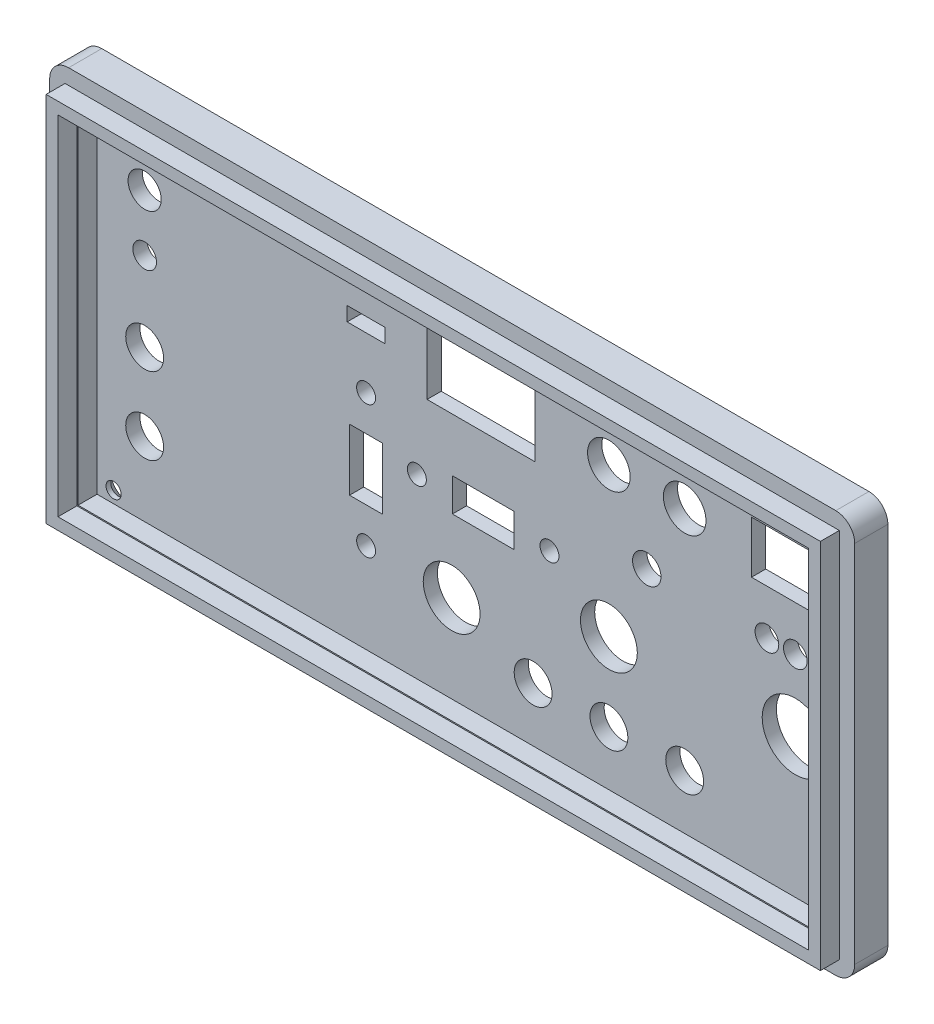
SolidWorks part; units mm, degrees
ref_plane "Спереди" through (0, 0, 0) normal (0, 0, 1) x (1, 0, 0)
ref_plane "Сверху" through (0, 0, 0) normal (0, 1, 0) x (1, 0, 0)
ref_plane "Справа" through (0, 0, 0) normal (1, 0, 0) x (0, 0, -1)
other "Configuration Table"
sketch "Эскиз1" plane through (0, 0, 0) normal (0, 0, 1) x (1, 0, 0)
  line L1 (-85, 42.5) -> (85, 42.5)
  line L2 (-85, 42.5) -> (-85, -42.5)
  line L3 (-85, -42.5) -> (85, -42.5)
  line L4 (85, 42.5) -> (85, -42.5)
  line L5 (-85, 42.5) -> (85, -42.5) construction
  line L6 (-85, -42.5) -> (85, 42.5) construction
  point P0 (0, 0)
  dimension "D1" = 170
  dimension "D2" = 85
extrude "Бобышка-Вытянуть1" add sketch "Эскиз1" along normal blind 3
sketch "Эскиз2" plane through (0, 0, 3) normal (0, 0, 1) x (1, 0, 0)
  line L1 (-85, 42.5) -> (85, 42.5)
  line L2 (-85, 42.5) -> (-85, -42.5)
  line L3 (-85, -42.5) -> (85, -42.5)
  line L4 (85, 42.5) -> (85, -42.5)
  line L5 (-85, 42.5) -> (85, -42.5) construction
  line L6 (-85, -42.5) -> (85, 42.5) construction
  point P0 (0, 0)
extrude "Вытянуть-Тонкостенный1" add sketch "Эскиз2" along normal blind 4 thin
sketch "Эскиз4" plane through (0, 0, 7) normal (0, 0, 1) x (1, 0, 0)
  line L1 (-81.75, 39.25) -> (81.75, 39.25)
  line L2 (-81.75, 39.25) -> (-81.75, -39.25)
  line L3 (-81.75, -39.25) -> (81.75, -39.25)
  line L4 (81.75, 39.25) -> (81.75, -39.25)
  line L5 (-81.75, 39.25) -> (81.75, -39.25) construction
  line L6 (-81.75, -39.25) -> (81.75, 39.25) construction
  point P0 (0, 0)
  dimension "D1" = 78.5
  dimension "D2" = 163.5
extrude "Вытянуть-Тонкостенный2" add sketch "Эскиз4" along normal blind 4 thin
fillet "Скругление1" radius 4 4 edges at (-85, -42.5, 3.5) (-85, 42.5, 3.5) (85, 42.5, 3.5) (85, -42.5, 3.5)
ref_plane "Плоскость1" through (82.5, -40, 37) normal (-1, 0, 0) x (0, 0, 1)
sketch "Эскиз7" plane through (0, 0, 38.5) normal (0, 0, 1) x (1, 0, 0)
  circle A0 centre (-75.5, 34) radius 1.6
sketch "Эскиз8" plane through (0, 0, 3) normal (0, 0, 1) x (1, 0, 0)
  circle A0 centre (-75.5, 34) radius 1.6
  circle A1 centre (75.5717, 35.0096) radius 1.6
  circle A2 centre (75.5717, -32.9904) radius 1.6
  circle A3 centre (-75.5, -34) radius 1.6
  dimension "D1" = 3.2
  dimension "D2" = 3.2
  dimension "D3" = 3.2
  dimension "D4" = 3.2
extrude "Вырез-Вытянуть1" cut sketch "Эскиз8" against normal blind 10
chamfer "Фаска1" distance 2 angle 45 4 edges at (77.1717, -32.9904, 0) (77.1717, 35.0096, 0) (-73.9, 34, 0) (-73.9, -34, 0)
sketch "Эскиз9" plane through (0, 0, 0) normal (0, 0, -1) x (-1, 0, 0)
  line L0 (-97.6837, 22.9271) -> (103.9627, 22.9271) construction
  line L1 (-68.4596, 22.9271) -> (-68.4596, -4.7615) construction
  line L2 (-97.6837, 7.9271) -> (103.9627, 7.9271) construction
  line L3 (-77.7096, 28.4271) -> (-59.2096, 28.4271)
  line L4 (-77.7096, 28.4271) -> (-77.7096, 17.4271)
  line L5 (-77.7096, 17.4271) -> (-59.2096, 17.4271)
  line L6 (-59.2096, 28.4271) -> (-59.2096, 17.4271)
  line L7 (-77.7096, 28.4271) -> (-59.2096, 17.4271) construction
  line L8 (-77.7096, 17.4271) -> (-59.2096, 28.4271) construction
  line L9 (-97.6837, -7.0729) -> (103.9627, -7.0729) construction
  circle A0 centre (-74.4596, 7.9271) radius 2.5
  circle A1 centre (-68.4596, 7.9271) radius 2.5
  circle A2 centre (-62.4596, 7.9271) radius 2.5
  circle A3 centre (-68.4596, -7.0729) radius 7
  point P7 (-68.4596, 22.9271)
  dimension "D1" = 30
  dimension "D2" = 11
  dimension "D3" = 15
extrude "Вырез-Оптопари" cut sketch "Эскиз9" against normal blind 10
sketch "Эскиз10" plane through (0, 0, 0) normal (0, 0, -1) x (-1, 0, 0)
  line L0 (-77.7096, 22.9271) -> (99.4949, 22.9271) construction
  line L1 (-77.7096, 28.4271) -> (-77.7096, 17.4271) construction
  line L2 (-74.4596, 7.9271) -> (86.7696, 7.9271) construction
  circle A0 centre (-45.0907, 22.9271) radius 4.5
  circle A1 centre (-29.0907, 22.9271) radius 4.5
  circle A2 centre (-37.0907, 7.9271) radius 3
  dimension "D1" = 16
  dimension "D2" = 8
extrude "Вырез-Стабілітрон" cut sketch "Эскиз10" against normal blind 10
sketch "Эскиз12" plane through (0, 0, 0) normal (0, 0, -1) x (-1, 0, 0)
  line L0 (-45.0907, 22.9271) -> (90.0896, 22.9271) construction
  line L1 (-45.5401, 0.9041) -> (54.3587, 0.9041) construction
  line L2 (-13.4907, 30.1771) -> (9.3093, 30.1771)
  line L3 (-13.4907, 30.1771) -> (-13.4907, 15.6771)
  line L4 (-13.4907, 15.6771) -> (9.3093, 15.6771)
  line L5 (9.3093, 30.1771) -> (9.3093, 15.6771)
  line L6 (-13.4907, 30.1771) -> (9.3093, 15.6771) construction
  line L7 (-13.4907, 15.6771) -> (9.3093, 30.1771) construction
  line L9 (-9.0401, 4.4041) -> (3.9599, 4.4041)
  line L10 (-9.0401, 4.4041) -> (-9.0401, -2.5959)
  line L11 (-9.0401, -2.5959) -> (3.9599, -2.5959)
  line L12 (3.9599, 4.4041) -> (3.9599, -2.5959)
  line L13 (-9.0401, 4.4041) -> (3.9599, -2.5959) construction
  line L14 (-9.0401, -2.5959) -> (3.9599, 4.4041) construction
  circle A0 centre (-16.5401, 0.9041) radius 2
  circle A1 centre (11.4599, 0.9041) radius 2
  point P3 (-2.0907, 22.9271)
  point P10 (-2.5401, 0.9041)
  dimension "D6" = 14
  dimension "D1" = 22.8
  dimension "D2" = 14.5
  dimension "D3" = 43
  dimension "D4" = 7
  dimension "D5" = 13
  dimension "D7" = 14
extrude "Вырез-Вольтметр" cut sketch "Эскиз12" against normal blind 10
sketch "Эскиз14" plane through (0, 0, 0) normal (0, 0, -1) x (-1, 0, 0)
  line L0 (-45.6627, 34.8723) -> (-45.6627, 33.8723)
  line L1 (-45.6627, 34.8723) -> (-39.6627, 34.8723)
  line L2 (-45.6627, 33.8723) -> (-39.6627, 33.8723)
  line L3 (-39.6627, 34.8723) -> (-39.6627, 37.8723)
  line L4 (-39.6627, 33.8723) -> (-39.6627, 30.8723)
  line L5 (-45.6627, 34.3723) -> (-30.2998, 34.3723) construction
  line L6 (-39.6627, 30.8723) -> (-34.9468, 33.8723)
  line L7 (-39.6627, 37.8723) -> (-34.9468, 34.8723)
  line L14 (-34.9468, 30.8723) -> (-34.9468, 33.8723)
  line L20 (-34.9468, 34.8723) -> (-34.9468, 37.6358)
  line L21 (-34.9468, 37.6358) -> (-36.1646, 37.6358)
  line L22 (-36.1646, 37.6358) -> (-36.1646, 38.3762)
  line L23 (-36.1646, 38.3762) -> (-34.0443, 38.3762)
  line L24 (-34.0443, 38.3762) -> (-34.0443, 34.8723)
  line L25 (-34.0443, 34.8723) -> (-30.2998, 34.8723)
  line L26 (-30.2998, 34.8723) -> (-30.2998, 33.8723)
  line L27 (-30.2998, 33.8723) -> (-34.0443, 33.8723)
  line L28 (-34.0443, 33.8723) -> (-34.0443, 30.8723)
  line L29 (-34.9468, 30.8723) -> (-34.0443, 30.8723)
extrude "Вырез-Символ стабілітрон" cut sketch "Эскиз14" against normal blind 1
sketch "Эскиз15" plane through (0, 0, 0) normal (0, 0, -1) x (-1, 0, 0)
  line L0 (-85, -25) -> (92.6455, -25) construction
  line L1 (-85, -38.5) -> (-85, 38.5) construction
  line L2 (-45.0907, 22.9271) -> (-45.0907, -33.3708) construction
  line L3 (-29.0907, 22.9271) -> (-29.0907, -33.3708) construction
  line L4 (-13.0907, 22.9271) -> (-13.0907, -33.3708) construction
  circle A0 centre (-45.0907, -25) radius 4
  circle A1 centre (-29.0907, -25) radius 4
  circle A2 centre (-13.0907, -25) radius 4
  circle A3 centre (-29.0907, -8.4792) radius 6
  dimension "D2" = 25
  dimension "D1" = 16
extrude "Вырез-MOSFET_TRIAC" cut sketch "Эскиз15" against normal blind 4
sketch "Эскиз16" plane through (0, 0, 0) normal (0, 0, -1) x (-1, 0, 0)
  text T0 "<b>G</b>"
  text T1 "<b>D</b>"
  text T2 "<b>S</b>"
  point P2 (0, 0)
  point P3 (0, 0)
  point P5 (-16.1508, -35.7077)
  point P6 (-14.9612, -33.6029)
  point P7 (0, 0)
  point P8 (-15.6018, -34.7011)
  point P9 (-47.7222, -34.7011)
extrude "Вырез-GDS" cut sketch "Эскиз16" against normal blind 1
sketch "Эскиз17" plane through (0, 0, 0) normal (0, 0, -1) x (-1, 0, 0)
  line L0 (-91.259, -18) -> (28.0286, -18) construction
  circle A0 centre (4.1179, -18) radius 6
  dimension "D1" = 18
extrude "Вырез-Нагрузочна лампа" cut sketch "Эскиз17" against normal blind 5
sketch "Эскиз18" plane through (0, 0, 0) normal (0, 0, -1) x (-1, 0, 0)
  line L0 (-77.7096, 22.9271) -> (77.7492, 22.9271) construction
  line L1 (-77.7096, 28.4271) -> (-77.7096, 17.4271) construction
  line L2 (22.1808, 22.9271) -> (22.1808, -29.9699) construction
  line L3 (18.1808, 24.4271) -> (26.1808, 24.4271)
  line L4 (18.1808, 24.4271) -> (18.1808, 21.4271)
  line L5 (18.1808, 21.4271) -> (26.1808, 21.4271)
  line L6 (26.1808, 24.4271) -> (26.1808, 21.4271)
  line L7 (18.1808, 24.4271) -> (26.1808, 21.4271) construction
  line L8 (18.1808, 21.4271) -> (26.1808, 24.4271) construction
  line L9 (11.4599, 0.9041) -> (11.4599, -7.0412) construction
  line L11 (18.6808, 2.9786) -> (25.6808, 2.9786)
  line L12 (18.6808, 2.9786) -> (18.6808, -10.0214)
  line L13 (18.6808, -10.0214) -> (25.6808, -10.0214)
  line L14 (25.6808, 2.9786) -> (25.6808, -10.0214)
  line L15 (18.6808, 2.9786) -> (25.6808, -10.0214) construction
  line L16 (18.6808, -10.0214) -> (25.6808, 2.9786) construction
  circle A0 centre (22.1808, 10.4786) radius 2
  circle A1 centre (22.1808, -17.5214) radius 2
  point P4 (22.1808, 22.9271)
  point P14 (22.1808, -3.5214)
  point P23 (0, 0)
  point P24 (0, 0)
  point P25 (22.1808, -3.5214)
  dimension "D6" = 14
  dimension "D1" = 8
  dimension "D2" = 3
  dimension "D3" = 10.721
  dimension "D4" = 7
  dimension "D5" = 13
  dimension "D7" = 14
extrude "Вырез-Вытянуть9" cut sketch "Эскиз18" against normal blind 5
sketch "Эскиз19" plane through (0, 0, 0) normal (0, 0, -1) x (-1, 0, 0)
  text T0 "<b>TL431</b>" font "Arial" height 3
  text T1 "<b>R A C</b>" font "Arial" height 3
  text T2 "<b>2.5V</b>"
  text T3 "<b>5V</b>"
  point P4 (27.1543, -8.3295)
extrude "Вырез-Вытянуть10" cut sketch "Эскиз19" against normal blind 1
sketch "Эскиз20" plane through (0, 0, 0) normal (0, 0, -1) x (-1, 0, 0)
  line L0 (68.9436, 46.521) -> (68.9436, -45.3564) construction
  circle A0 centre (68.9436, -20.8799) radius 4
  circle A1 centre (68.9436, -4.605) radius 4
  circle A2 centre (68.9436, 24.1386) radius 3.5
  circle A3 centre (68.9436, 12.1949) radius 2.5
extrude "Вырез-Вытянуть11" cut sketch "Эскиз20" against normal blind 5
sketch "Эскиз21" plane through (0, 0, 0) normal (0, 0, -1) x (-1, 0, 0)
  text T0 "<b>Lx</b>"
extrude "Вырез-Вытянуть12" cut sketch "Эскиз21" against normal blind 1
equation "\"D3@Эскиз8\"=\"D1@Эскиз8\""
equation "\"D2@Эскиз8\"=\"D1@Эскиз8\""
equation "\"D4@Эскиз8\"=\"D1@Эскиз8\""
